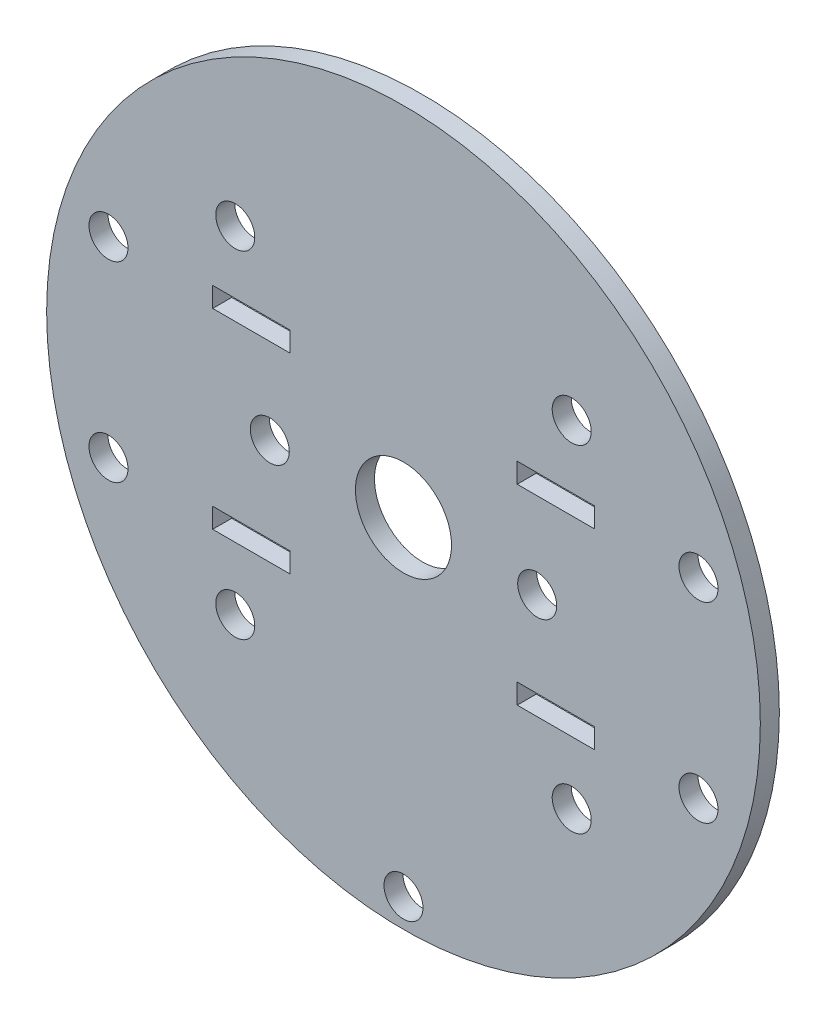
SolidWorks part; units mm, degrees
ref_plane "前视基准面" through (0, 0, 0) normal (0, 0, 1) x (1, 0, 0)
ref_plane "上视基准面" through (0, 0, 0) normal (0, 1, 0) x (1, 0, 0)
ref_plane "右视基准面" through (0, 0, 0) normal (1, 0, 0) x (0, 0, -1)
sketch "草图1" plane through (0, 0, 0) normal (0, 0, 1) x (1, 0, 0)
  line L0 (0, 0) -> (0, -37.5) construction
  line L1 (0, 0) -> (-28.479, -28.479) construction
  line L2 (3, -40.5) -> (-3, -40.5) construction
  line L3 (3, -40.5) -> (3, -34.5) construction
  line L4 (3, -34.5) -> (-3, -34.5) construction
  line L5 (-3, -40.5) -> (-3, -34.5) construction
  line L6 (3, -40.5) -> (-3, -34.5) construction
  line L7 (3, -34.5) -> (-3, -40.5) construction
  line L8 (20.05, -11.1) -> (20.05, -9)
  line L9 (11.95, -9) -> (20.05, -9)
  line L10 (11.95, -11.1) -> (11.95, -9)
  line L11 (11.95, -11.1) -> (20.05, -11.1)
  line L12 (0, 0) -> (37.5, 0) construction
  line L13 (11.95, 11.1) -> (11.95, 9)
  line L14 (20.05, 11.1) -> (20.05, 9)
  line L15 (11.95, 9) -> (20.05, 9)
  line L16 (11.95, 11.1) -> (20.05, 11.1)
  line L17 (-20.05, 11.1) -> (-20.05, 9)
  line L18 (-11.95, 11.1) -> (-11.95, 9)
  line L19 (-11.95, 9) -> (-20.05, 9)
  line L20 (-11.95, 11.1) -> (-20.05, 11.1)
  line L21 (-11.95, -11.1) -> (-11.95, -9)
  line L22 (-20.05, -11.1) -> (-20.05, -9)
  line L23 (-11.95, -9) -> (-20.05, -9)
  line L24 (-11.95, -11.1) -> (-20.05, -11.1)
  line L25 (-11.95, -9) -> (-20.05, -11.1) construction
  line L26 (-16, -10.05) -> (-31, -10.05) construction
  circle A0 centre (0, 0) radius 37.5
  circle A1 centre (0, 0) radius 5.05
  circle A2 centre (-3, -34.5) radius 1.55 construction
  circle A3 centre (3, -34.5) radius 1.55 construction
  circle A4 centre (0, 0) radius 25 construction
  circle A5 centre (-17.6777, -17.6777) radius 2.05
  circle A6 centre (-17.6777, 17.6777) radius 2.05
  circle A7 centre (17.6777, 17.6777) radius 2.05
  circle A8 centre (17.6777, -17.6777) radius 2.05
  circle A10 centre (-31, -10.05) radius 2.05
  circle A11 centre (-31, 10.05) radius 2.05
  circle A12 centre (31, 10.05) radius 2.05
  circle A13 centre (31, -10.05) radius 2.05
  circle A14 centre (0, 0) radius 14.05 construction
  circle A15 centre (14.05, 0) radius 2.05
  circle A16 centre (-14.05, 0) radius 2.05
  circle A18 centre (0, -34.5) radius 2.05
  dimension "D1" = 75
  dimension "D2" = 10.1
  dimension "D5" = 50
  dimension "D7" = 4
  dimension "D8" = 18
  dimension "D9" = 3
  dimension "D3" = 6
  dimension "D4" = 6
  dimension "D6" = 45
extrude "凸台-拉伸1" add sketch "草图1" along normal blind 2
